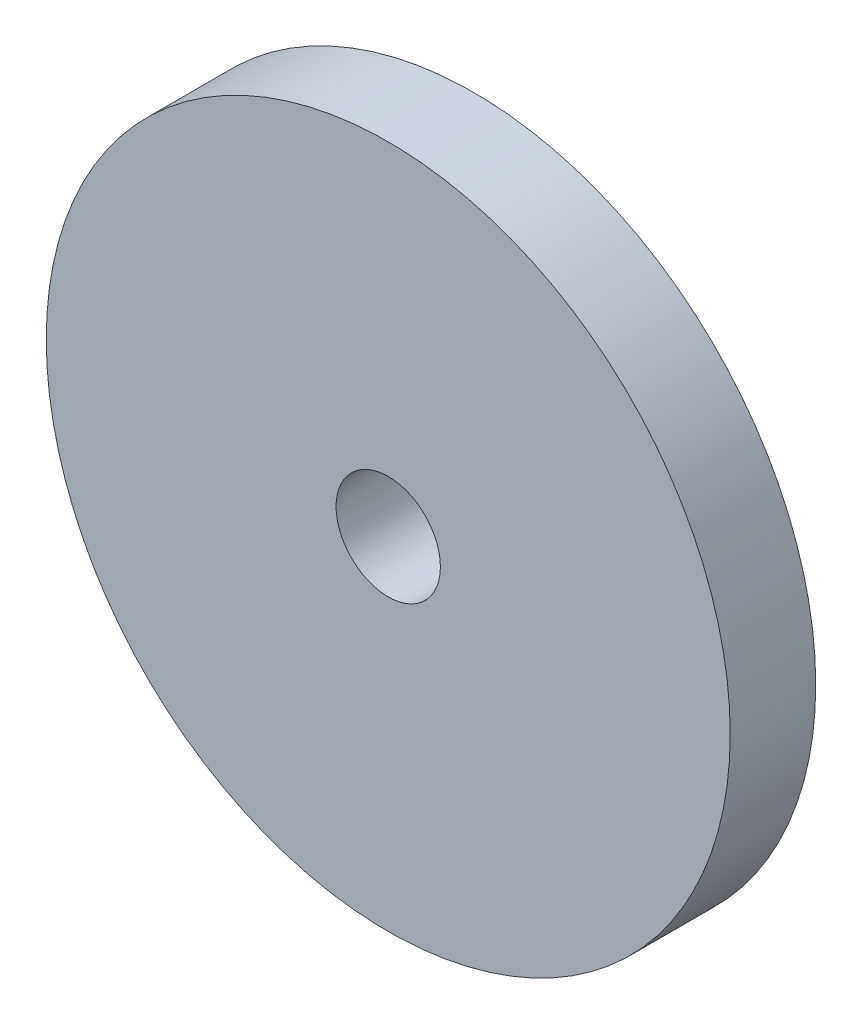
SolidWorks part; units mm, degrees
ref_plane "Front Plane" through (0, 0, 0) normal (0, 0, 1) x (1, 0, 0)
ref_plane "Top Plane" through (0, 0, 0) normal (0, 1, 0) x (1, 0, 0)
ref_plane "Right Plane" through (0, 0, 0) normal (1, 0, 0) x (0, 0, -1)
sketch "Sketch1" plane through (0, 0, 0) normal (0, 0, 1) x (1, 0, 0)
  circle A0 centre (0, 0) radius 3.05
  circle A1 centre (0, 0) radius 20
  dimension "D1" = 6.1
  dimension "D2" = 40
extrude "Boss-Extrude1" add sketch "Sketch1" along normal blind 5
